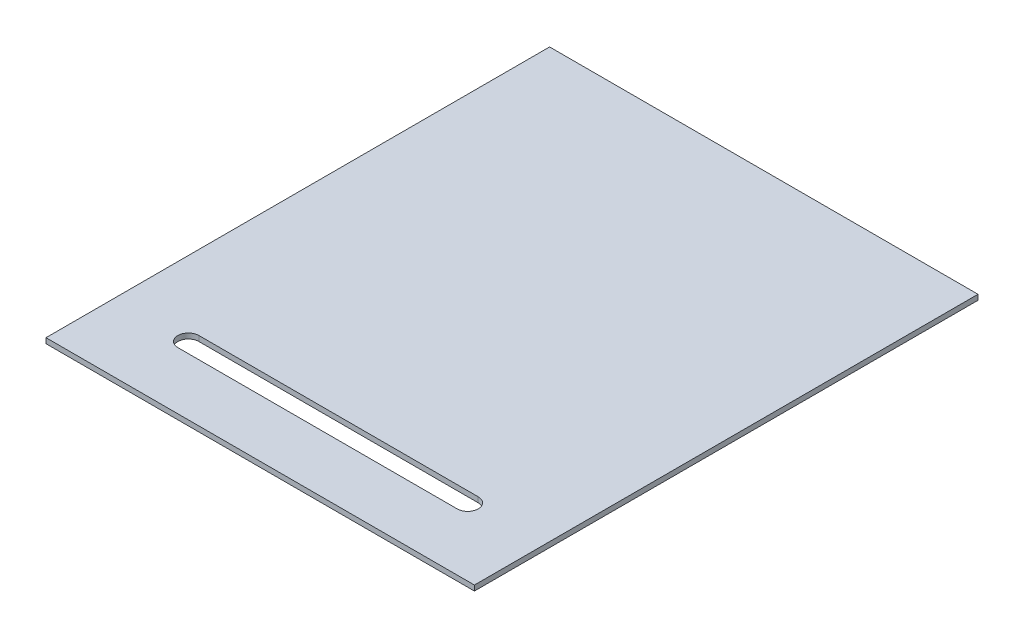
SolidWorks part; units mm, degrees
material "PC High Viscosity"
ref_plane "Front Plane" through (0, 0, 0) normal (0, 0, 1) x (1, 0, 0)
ref_plane "Top Plane" through (0, 0, 0) normal (0, 1, 0) x (1, 0, 0)
ref_plane "Right Plane" through (0, 0, 0) normal (1, 0, 0) x (0, 0, -1)
sketch "Sketch1" plane through (0, 0, 0) normal (0, 1, 0) x (1, 0, 0)
  line L0 (-84.455, -111.252) -> (84.455, -111.252) construction
  line L1 (-129.54, 152.273) -> (129.54, 152.273)
  line L2 (-129.54, 152.273) -> (-129.54, -152.273)
  line L3 (-129.54, -152.273) -> (129.54, -152.273)
  line L4 (129.54, 152.273) -> (129.54, -152.273)
  line L5 (-129.54, 152.273) -> (129.54, -152.273) construction
  line L6 (-129.54, -152.273) -> (129.54, 152.273) construction
  line L7 (-84.455, -104.902) -> (84.455, -104.902)
  line L8 (-84.455, -117.602) -> (84.455, -117.602)
  arc A0 (-84.455, -104.902) -> (-84.455, -117.602) centre (-84.455, -111.252) ccw
  arc A1 (84.455, -117.602) -> (84.455, -104.902) centre (84.455, -111.252) ccw
  point P0 (0, 0)
  point P8 (0, -111.252)
  point P13 (0, -111.252)
  point P14 (0, -152.273)
  point P15 (0, 0)
  dimension "D4" = 6.35
  dimension "D1" = 259.08
  dimension "D2" = 304.546
  dimension "D3" = 168.91
  dimension "D5" = 41.021
extrude "Boss-Extrude1" add sketch "Sketch1" along normal blind 3.175
